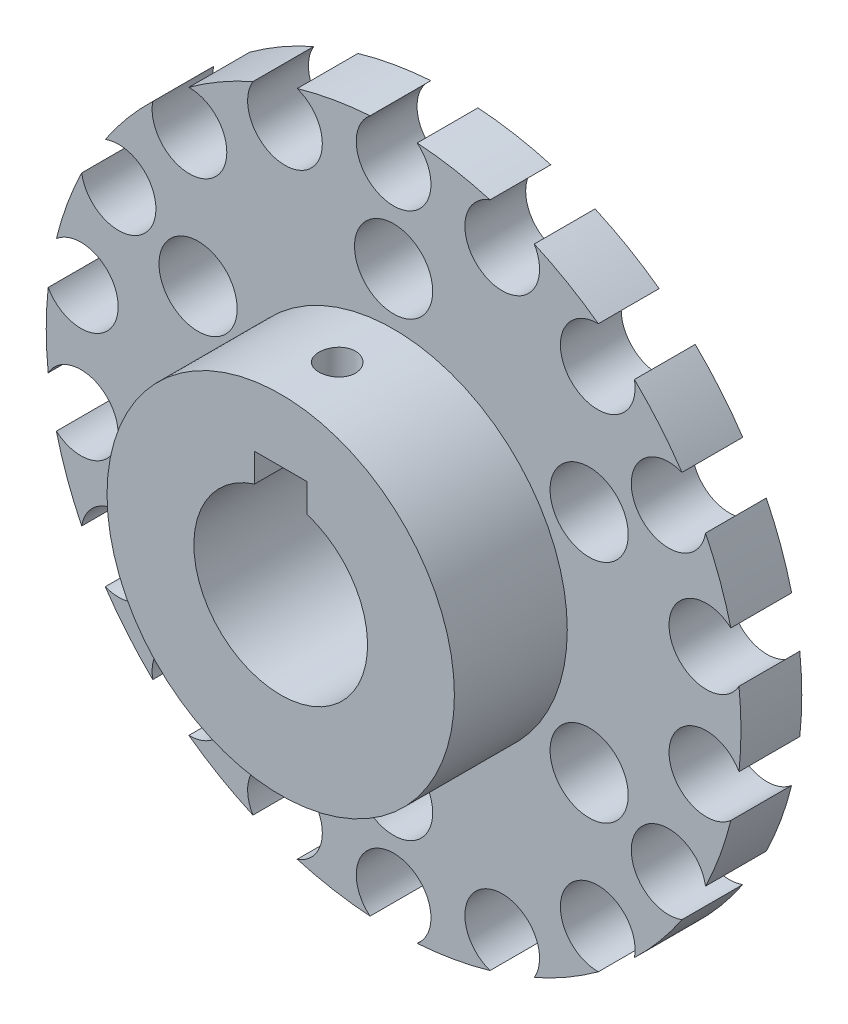
SolidWorks part; units mm, degrees
ref_plane "前视基准面" through (0, 0, 0) normal (0, 0, 1) x (1, 0, 0)
ref_plane "上视基准面" through (0, 0, 0) normal (0, 1, 0) x (1, 0, 0)
ref_plane "右视基准面" through (0, 0, 0) normal (1, 0, 0) x (0, 0, -1)
sketch "草图1" plane through (0, 0, 0) normal (0, 0, 1) x (1, 0, 0)
  circle A0 centre (0, 0) radius 40
extrude "凸台-拉伸1" add sketch "草图1" along normal blind 7
ref_plane "基准面1" through (0, 0, 7) normal (0, 0, 1) x (1, 0, 0)
sketch "草图2" plane through (0, 0, 7) normal (0, 0, 1) x (1, 0, 0)
  circle A0 centre (0, 0) radius 20
extrude "凸台-拉伸2" add sketch "草图2" along normal blind 13
sketch "草图3" plane through (0, 0, 0) normal (0, 0, 1) x (1, 0, 0)
  circle A0 centre (0, 36.57) radius 4.3
  circle A1 centre (-12.5077, 34.3646) radius 4.3
  circle A2 centre (-23.5067, 28.0142) radius 4.3
  circle A3 centre (-31.6705, 18.285) radius 4.3
  circle A4 centre (-36.0144, 6.3503) radius 4.3
  circle A5 centre (-36.0144, -6.3503) radius 4.3
  circle A6 centre (-31.6705, -18.285) radius 4.3
  circle A7 centre (-23.5067, -28.0142) radius 4.3
  circle A8 centre (-12.5077, -34.3646) radius 4.3
  circle A9 centre (0, -36.57) radius 4.3
  circle A10 centre (12.5077, -34.3646) radius 4.3
  circle A11 centre (23.5067, -28.0142) radius 4.3
  circle A12 centre (31.6705, -18.285) radius 4.3
  circle A13 centre (36.0144, -6.3503) radius 4.3
  circle A14 centre (36.0144, 6.3503) radius 4.3
  circle A15 centre (31.6705, 18.285) radius 4.3
  circle A16 centre (23.5067, 28.0142) radius 4.3
  circle A17 centre (12.5077, 34.3646) radius 4.3
extrude "切除-拉伸1" cut sketch "草图3" along normal through all
sketch "草图4" plane through (0, 0, 0) normal (0, 0, 1) x (1, 0, 0)
  circle A0 centre (0, 26) radius 4.5
  circle A1 centre (-22.5167, 13) radius 4.5
  circle A2 centre (-22.5167, -13) radius 4.5
  circle A3 centre (0, -26) radius 4.5
  circle A4 centre (22.5167, -13) radius 4.5
  circle A5 centre (22.5167, 13) radius 4.5
extrude "切除-拉伸2" cut sketch "草图4" along normal through all
sketch "草图5" plane through (0, 0, 0) normal (0, 0, 1) x (1, 0, 0)
  circle A0 centre (0, 0) radius 10
extrude "切除-拉伸3" cut sketch "草图5" along normal through all
sketch "草图6" plane through (0, 0, 0) normal (0, 0, 1) x (1, 0, 0)
  line L0 (-3, 0) -> (3, 0)
  line L1 (3, 0) -> (3, 12.8)
  line L2 (3, 12.8) -> (-3, 12.8)
  line L3 (-3, 12.8) -> (-3, 0)
extrude "切除-拉伸4" cut sketch "草图6" along normal through all
ref_plane "基准面2" through (0, 13.5, 0) normal (0, 1, 0) x (1, 0, 0)
sketch "草图8" plane through (0, 13.5, 0) normal (0, 1, 0) x (1, 0, 0)
  circle A0 centre (0, -13.5) radius 2.1
extrude "切除-拉伸6" cut sketch "草图8" against normal mid plane 20
